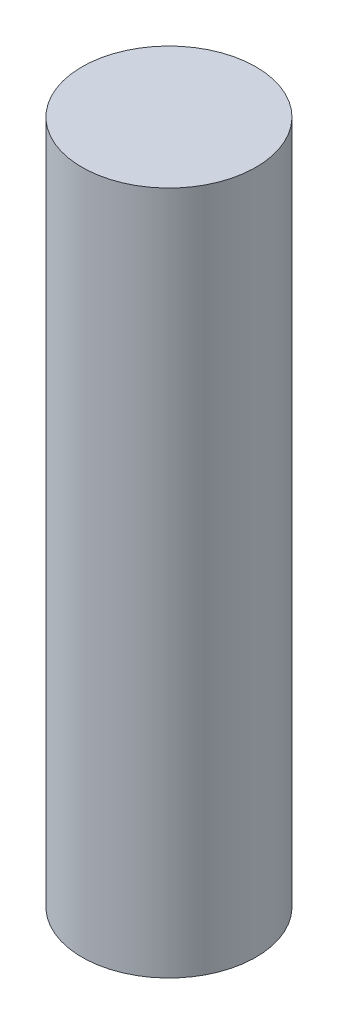
SolidWorks part; units mm, degrees
ref_plane "Front Plane" through (0, 0, 0) normal (0, 0, 1) x (1, 0, 0)
ref_plane "Top Plane" through (0, 0, 0) normal (0, 1, 0) x (1, 0, 0)
ref_plane "Right Plane" through (0, 0, 0) normal (1, 0, 0) x (0, 0, -1)
sketch "Sketch1" plane through (0, 0, 0) normal (0, 1, 0) x (1, 0, 0)
  circle A0 centre (0, 0) radius 14.5
  dimension "D1" = 29
extrude "Boss-Extrude1" add sketch "Sketch1" along normal blind 114
sketch "Sketch2" plane through (0, 0, 0) normal (0, 1, 0) x (1, 0, 0)
  circle A0 centre (0, 0) radius 12.5
  dimension "D1" = 25
extrude "Cut-Extrude2" cut sketch "Sketch2" along normal blind 105 contours A0
